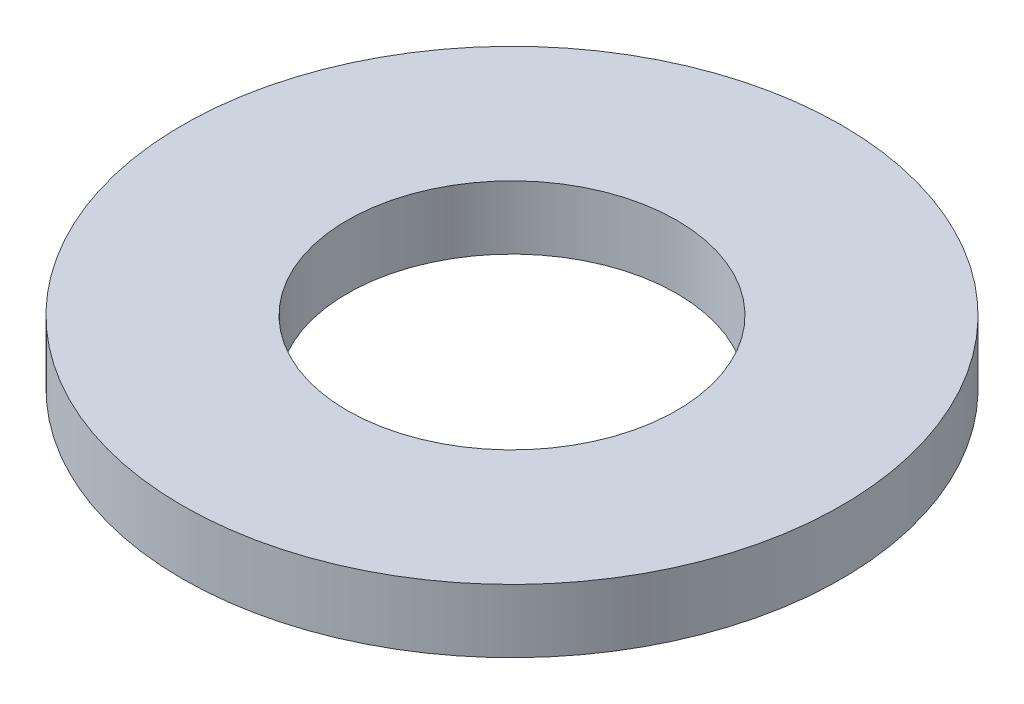
SolidWorks part; units mm, degrees
ref_plane "Front Plane" through (0, 0, 0) normal (0, 0, 1) x (1, 0, 0)
ref_plane "Top Plane" through (0, 0, 0) normal (0, 1, 0) x (1, 0, 0)
ref_plane "Right Plane" through (0, 0, 0) normal (1, 0, 0) x (0, 0, -1)
sketch "Sketch1" plane through (0, 0, 0) normal (0, 1, 0) x (1, 0, 0)
  circle A0 centre (5.5848, 0) radius 4
  circle A1 centre (5.5848, 0) radius 2
  dimension "D1" = 8
  dimension "D2" = 4
extrude "Boss-Extrude1" add sketch "Sketch1" along normal blind 0.77
